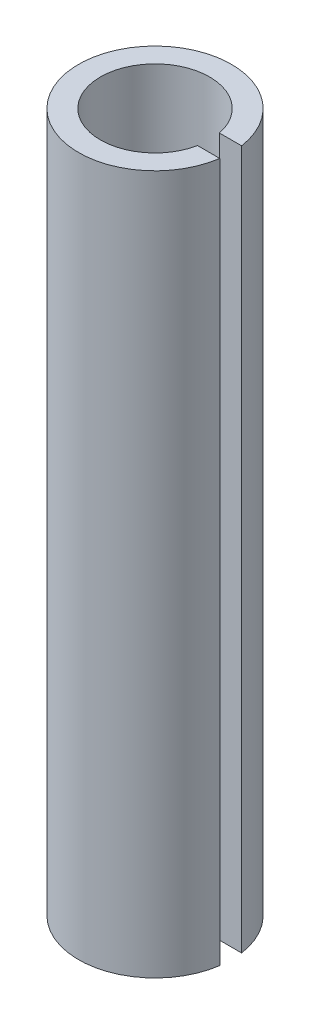
SolidWorks part; units mm, degrees
ref_plane "Front Plane" through (0, 0, 0) normal (0, 0, 1) x (1, 0, 0)
ref_plane "Top Plane" through (0, 0, 0) normal (0, 1, 0) x (1, 0, 0)
ref_plane "Right Plane" through (0, 0, 0) normal (1, 0, 0) x (0, 0, -1)
sketch "Sketch1" plane through (0, 0, 0) normal (0, 1, 0) x (1, 0, 0)
  line L0 (2.4495, 0.5) -> (3.4641, 0.5)
  line L1 (2.4495, -0.5) -> (3.4641, -0.5)
  line L2 (0, 0) -> (3.5, 0) construction
  circle A0 centre (0, 0) radius 3.5
  circle A1 centre (0, 0) radius 2.5
  dimension "D1" = 5
  dimension "D2" = 7
  dimension "D3" = 1
  dimension "D4" = 0.5
extrude "Boss-Extrude1" add sketch "Sketch1" along normal blind 32 contours A1 L0 A0 L1
